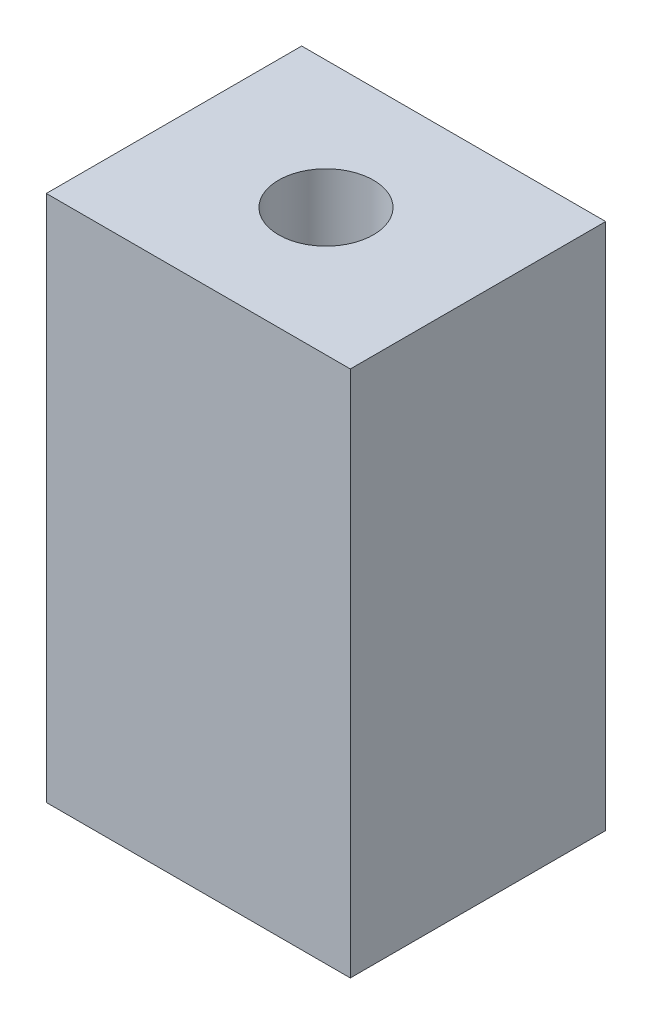
SolidWorks part; units mm, degrees
material "ASTM A36 Steel"
ref_plane "Front Plane" through (0, 0, 0) normal (0, 0, 1) x (1, 0, 0)
ref_plane "Top Plane" through (0, 0, 0) normal (0, 1, 0) x (1, 0, 0)
ref_plane "Right Plane" through (0, 0, 0) normal (1, 0, 0) x (0, 0, -1)
sketch "Sketch1" plane through (0, 0, 0) normal (0, 1, 0) x (1, 0, 0)
  line L0 (12.7, -10.668) -> (12.7, 0) construction
  line L1 (0, 0) -> (25.4, 0)
  line L2 (0, 0) -> (0, -21.336)
  line L3 (0, -21.336) -> (25.4, -21.336)
  line L4 (25.4, 0) -> (25.4, -21.336)
  line L5 (12.7, -10.668) -> (12.7, -21.336) construction
  line L6 (12.7, -10.668) -> (0, -10.668) construction
  line L7 (12.7, -10.668) -> (25.4, -10.668) construction
  circle A0 centre (12.7, -10.668) radius 3.9624
  dimension "D3" = 7.9248
  dimension "D1" = 25.4
  dimension "D2" = 21.336
extrude "Boss-Extrude1" add sketch "Sketch1" along normal blind 44.069
ref_plane "Plane1" through (12.7, 0, 0) normal (-1, 0, 0) x (0, 0, 1)
ref_plane "Plane2" through (0, 0, 10.668) normal (0, 0, -1) x (-1, 0, 0)
sketch "Sketch3" plane through (0, 0, 0) normal (-1, 0, 0) x (0, 0, 1)
  line L0 (10.668, 0) -> (10.668, 44.069) construction
  line L1 (0, 0) -> (21.336, 0) construction
  line L2 (0, 44.069) -> (21.336, 44.069) construction
  line L3 (16.1798, 32.258) -> (10.668, 32.258) construction
  line L4 (5.1562, 19.558) -> (10.668, 19.558) construction
  circle A0 centre (16.1798, 32.258) radius 2.286
  circle A1 centre (5.1562, 19.558) radius 2.286
  dimension "D4" = 4.572
  dimension "D1" = 12.7
  dimension "D2" = 5.5118
  dimension "D3" = 32.258
extrude "Cut-Extrude2" cut sketch "Sketch3" against normal blind 3.175
